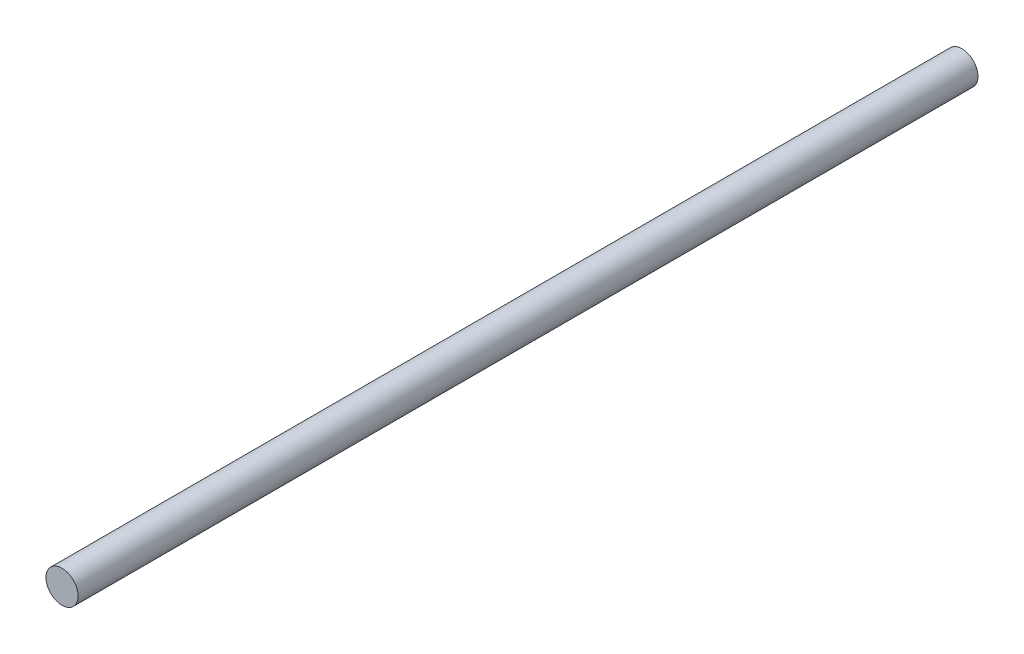
SolidWorks part; units mm, degrees
ref_plane "Plan de face" through (0, 0, 0) normal (0, 0, 1) x (1, 0, 0)
ref_plane "Plan de dessus" through (0, 0, 0) normal (0, 1, 0) x (1, 0, 0)
ref_plane "Plan de droite" through (0, 0, 0) normal (1, 0, 0) x (0, 0, -1)
sketch "Esquisse1" plane through (0, 0, 0) normal (0, 0, 1) x (1, 0, 0)
  circle A0 centre (0, 0) radius 4
  dimension "D1" = 8
extrude "Boss.-Extru.1" add sketch "Esquisse1" along normal blind 224
